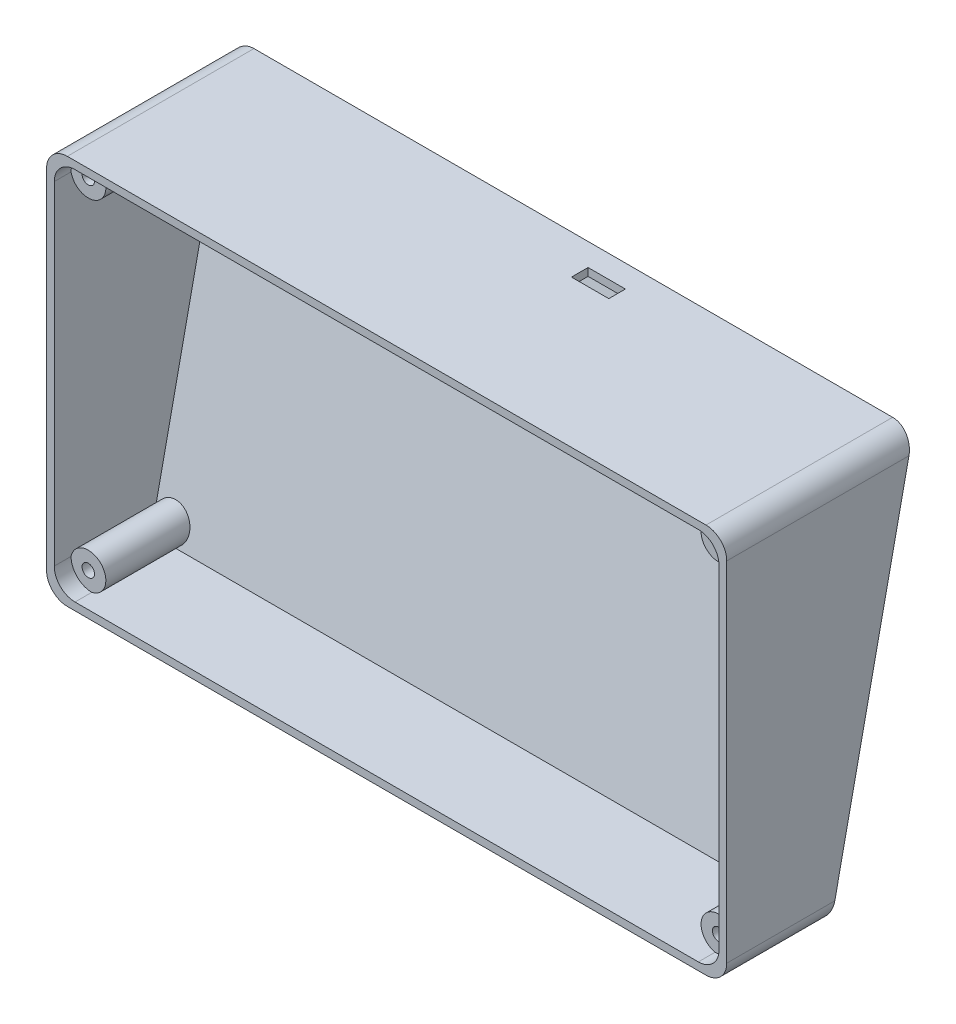
SolidWorks part; units mm, degrees
material "Nylon 101"
ref_plane "Ebene vorne" through (0, 0, 0) normal (0, 0, 1) x (1, 0, 0)
ref_plane "Ebene oben" through (0, 0, 0) normal (0, 1, 0) x (1, 0, 0)
ref_plane "Ebene rechts" through (0, 0, 0) normal (1, 0, 0) x (0, 0, -1)
sketch "Skizze1" plane through (0, 0, 0) normal (0, 0, 1) x (1, 0, 0)
  line L1 (-82, -47) -> (82, -47)
  line L2 (-82, -47) -> (-82, 47)
  line L3 (-82, 47) -> (82, 47)
  line L4 (82, -47) -> (82, 47)
  line L5 (-82, -47) -> (82, 47) construction
  line L6 (-82, 47) -> (82, -47) construction
  point P0 (0, 0)
  dimension "D1" = 164
  dimension "D2" = 94
extrude "Aufsatz-Linear austragen1" add sketch "Skizze1" along normal blind 25
sketch "Skizze2" plane through (82, 0, 0) normal (1, 0, 0) x (0, 0, -1)
  line L0 (0, -47) -> (0, 47)
  line L1 (0, 47) -> (20, 47)
  line L2 (20, 47) -> (0, -47)
  dimension "D1" = 20
extrude "Aufsatz-Linear austragen2" add sketch "Skizze2" against normal up to vertex (164 mm away) up to point (-82, 47, 0)
sketch "Skizze3" plane through (0, 0, 25) normal (0, 0, 1) x (1, 0, 0)
  line L1 (-75.15, -45.15) -> (75.15, -45.15)
  line L2 (-80.15, -40.15) -> (-80.15, 40.15)
  line L3 (-75.15, 45.15) -> (75.15, 45.15)
  line L4 (80.15, -40.15) -> (80.15, 40.15)
  line L5 (-80.15, -45.15) -> (80.15, 45.15) construction
  line L6 (-80.15, 45.15) -> (80.15, -45.15) construction
  arc A0 (80.15, 40.15) -> (75.15, 45.15) centre (75.15, 40.15) ccw
  arc A1 (80.15, -40.15) -> (75.15, -45.15) centre (75.15, -40.15) cw
  arc A2 (-80.15, -40.15) -> (-75.15, -45.15) centre (-75.15, -40.15) ccw
  arc A3 (-80.15, 40.15) -> (-75.15, 45.15) centre (-75.15, 40.15) cw
  point P1 (0, 0)
  dimension "D3" = 5
  dimension "D1" = 160.3
  dimension "D2" = 90.3
extrude "Schnitt-Linear austragen1" cut sketch "Skizze3" against normal offset from surface (24.4127 mm away) 2
sketch "Skizze4" plane through (0, 0, 25) normal (0, 0, 1) x (1, 0, 0)
  line L0 (75.15, 45.15) -> (-75.15, 45.15) construction
  line L1 (-80.15, 40.15) -> (-80.15, -40.15) construction
  line L2 (-75.15, -45.15) -> (75.15, -45.15) construction
  line L3 (80.15, -40.15) -> (80.15, 40.15) construction
  circle A0 centre (-76, 41) radius 1.5
  circle A1 centre (-76, 41) radius 4.2362
  circle A2 centre (-76, -41) radius 1.5
  circle A3 centre (-76, -41) radius 4.2362
  circle A4 centre (76, -41) radius 1.5
  circle A5 centre (76, -41) radius 4.2362
  circle A6 centre (76, 41) radius 1.5
  circle A7 centre (76, 41) radius 4.2362
  point P11 (-96.865, -34.1701)
  point P12 (-76, -41.965)
  point P18 (76.6885, -41)
  point P24 (76, 38.7455)
  point P25 (76, 41)
  point P26 (0, 0)
  dimension "D3" = 3
  dimension "D4" = 3
  dimension "D7" = 3
  dimension "D10" = 3
  dimension "D1" = 4.15
  dimension "D2" = 4.15
  dimension "D5" = 4.15
  dimension "D6" = 4.15
  dimension "D8" = 4.15
  dimension "D9" = 4.15
  dimension "D11" = 4.15
  dimension "D12" = 4.15
extrude "Aufsatz-Linear austragen3" add sketch "Skizze4" against normal up to surface (41.6786 mm away)
sketch "Skizze6" plane through (0, 0, 25) normal (0, 0, 1) x (1, 0, 0)
  line L0 (-75.15, -45.15) -> (75.15, -45.15)
  line L1 (-80.15, -40.15) -> (-80.15, 40.15)
  line L2 (-75.15, 45.15) -> (75.15, 45.15)
  line L3 (80.15, -40.15) -> (80.15, 40.15)
  line L4 (-80.15, -45.15) -> (80.15, 45.15) construction
  line L5 (-80.15, 45.15) -> (80.15, -45.15) construction
  arc A0 (80.15, 40.15) -> (75.15, 45.15) centre (75.15, 40.15) ccw
  arc A1 (80.15, -40.15) -> (75.15, -45.15) centre (75.15, -40.15) cw
  arc A2 (-80.15, -40.15) -> (-75.15, -45.15) centre (-75.15, -40.15) ccw
  arc A3 (-80.15, 40.15) -> (-75.15, 45.15) centre (-75.15, 40.15) cw
  point P0 (0, 0)
  point P20 (-132.9544, 49.8211)
  dimension "D3" = 5
  dimension "D1" = 160.3
  dimension "D2" = 90.3
  dimension "D4" = 0
  dimension "D5" = 0
extrude "Schnitt-Linear austragen2" cut sketch "Skizze6" against normal blind 4.05
fillet "Verrundung1" radius 5 4 edges at (82, 47, 2.5) (-82, 47, 2.5) (-82, -47, 12.5) (82, -47, 12.5)
sketch "Skizze7" plane through (0, 47, 0) normal (0, 1, 0) x (1, 0, 0)
  line L0 (75.15, 17.5616) -> (-75.15, 17.5616) construction
  line L1 (9, 14.5616) -> (18, 14.5616)
  line L2 (9, 14.5616) -> (9, 10.5616)
  line L3 (9, 10.5616) -> (18, 10.5616)
  line L4 (18, 14.5616) -> (18, 10.5616)
  line L5 (9, 14.5616) -> (18, 10.5616) construction
  line L6 (9, 10.5616) -> (18, 14.5616) construction
  point P0 (13.5, 12.5616)
  dimension "D1" = 13.5
  dimension "D2" = 3
  dimension "D3" = 9
  dimension "D4" = 4
extrude "Schnitt-Linear austragen4" cut sketch "Skizze7" against normal blind 4.05
sketch "Skizze8" plane through (0, -2.0355, -9.5669) normal (0, -0.2081, -0.9781) x (-1, 0, 0)
  line L0 (-82, -40.8591) -> (-82, 45.0212) construction
  line L1 (77, 50.1331) -> (-77, 50.1331) construction
  line L2 (82, -40.8591) -> (82, 45.0212) construction
  line L3 (77, -45.971) -> (-77, -45.971) construction
  circle A0 centre (-72, 40.1331) radius 5.5
  circle A1 centre (72, 40.1331) radius 5.5
  circle A2 centre (72, -35.971) radius 5.5
  circle A3 centre (-72, -35.971) radius 5.5
  point P8 (71.0051, 40.1331)
  point P13 (73.1884, -34.4377)
  point P14 (72, -35.6758)
  point P19 (-72, -35.971)
  dimension "D1" = 11
  dimension "D4" = 11
  dimension "D7" = 11
  dimension "D10" = 11
  dimension "D2" = 10
  dimension "D3" = 10
  dimension "D5" = 10
  dimension "D6" = 10
  dimension "D8" = 10
  dimension "D9" = 10
  dimension "D11" = 10
  dimension "D12" = 10
extrude "Schnitt-Linear austragen5" cut sketch "Skizze8" against normal blind 1
